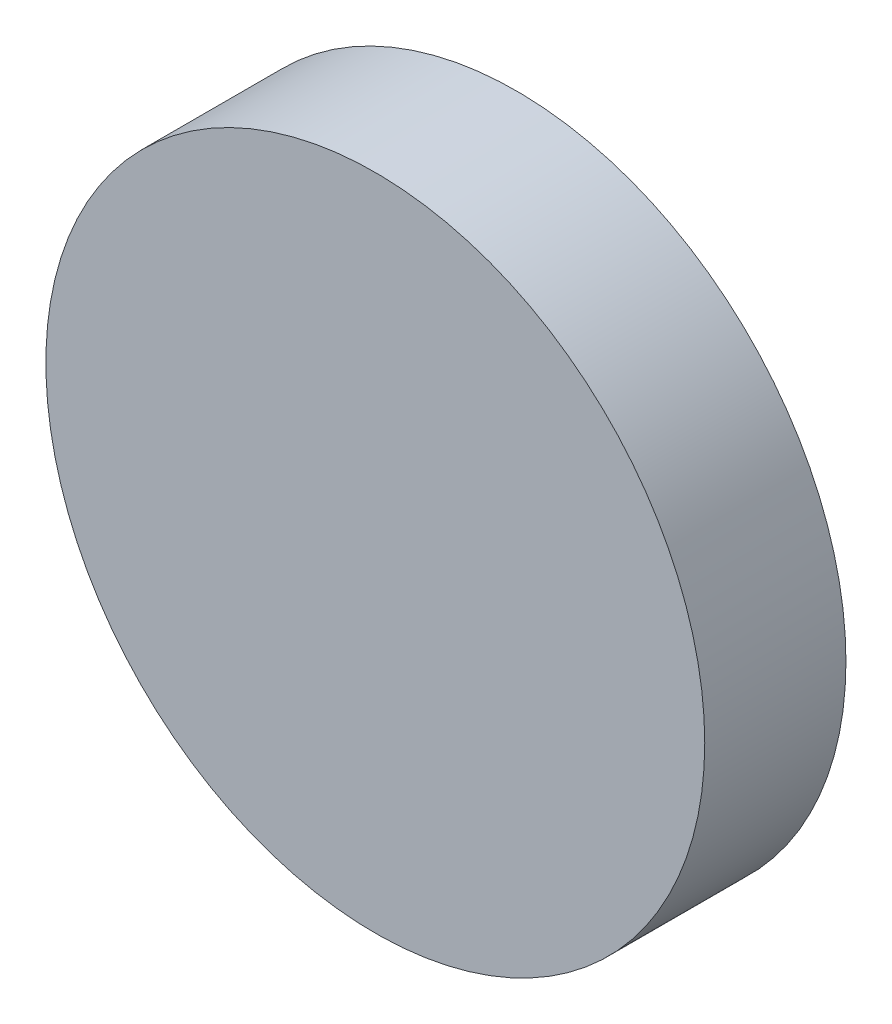
SolidWorks part; units mm, degrees
material "Acrylic (Medium-high impact)"
ref_plane "Front Plane" through (0, 0, 0) normal (0, 0, 1) x (1, 0, 0)
ref_plane "Top Plane" through (0, 0, 0) normal (0, 1, 0) x (1, 0, 0)
ref_plane "Right Plane" through (0, 0, 0) normal (1, 0, 0) x (0, 0, -1)
sketch "Sketch1" plane through (0, 0, 0) normal (0, 0, 1) x (1, 0, 0)
  circle A0 centre (0, 0) radius 7
  dimension "D1" = 14
extrude "Laser Base Body" add sketch "Sketch1" along normal blind 3
